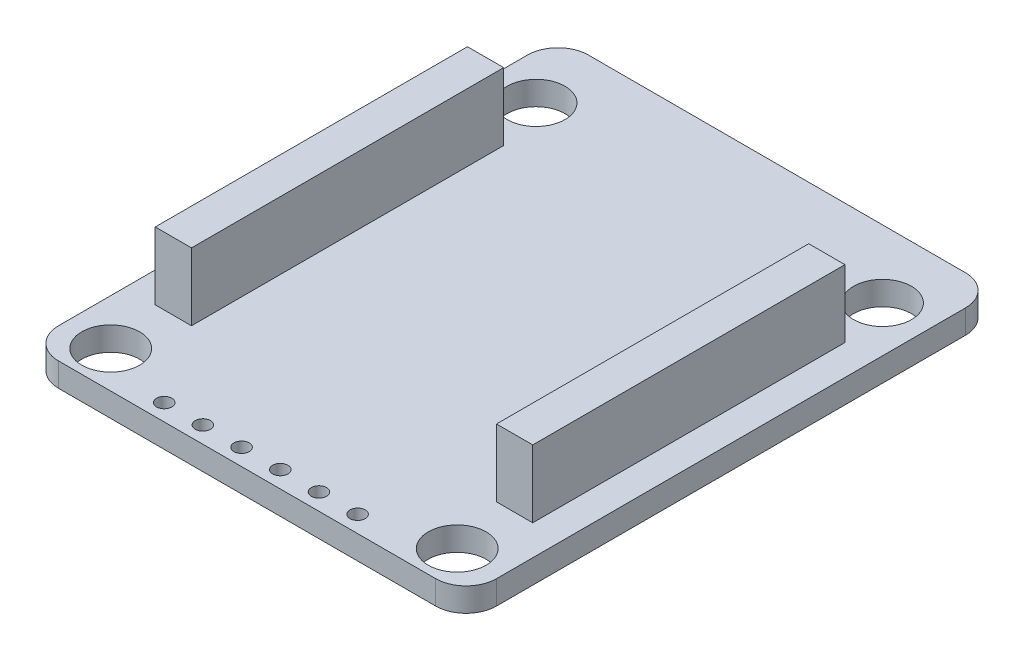
SolidWorks part; units mm, degrees
ref_plane "Front" through (0, 0, 0) normal (0, 0, 1) x (1, 0, 0)
ref_plane "Top" through (0, 0, 0) normal (0, 1, 0) x (1, 0, 0)
ref_plane "Right" through (0, 0, 0) normal (1, 0, 0) x (0, 0, -1)
sketch "Sketch1" plane through (0, 0, 0) normal (0, 1, 0) x (1, 0, 0)
  line L0 (-14.7218, -21.8882) -> (15.2782, -21.8882) construction
  line L1 (-14.38, -17.395) -> (14.38, -17.395)
  line L2 (-14.38, -17.395) -> (-14.38, 17.395)
  line L3 (-14.38, 17.395) -> (14.38, 17.395)
  line L4 (14.38, -17.395) -> (14.38, 17.395)
  line L5 (-14.38, -17.395) -> (14.38, 17.395) construction
  line L6 (-14.38, 17.395) -> (14.38, -17.395) construction
  point P0 (0, 0)
  dimension "D1" = 34.79
  dimension "D2" = 28.76
  dimension "D3" = 30
extrude "PCB" add sketch "Sketch1" along normal blind 1.56
hole_wizard "Ø3.8 (3.8) Diameter Hole4" positions "Sketch4" profile "Sketch5" hole size "Ø3.8" standard "ANSI Metric" end condition through all
sketch "Sketch4" plane through (0, 1.56, 0) normal (0, 1, 0) x (1, 0, 0)
  line L1 (-11.375, 12.955) -> (11.375, 12.955)
  line L2 (-11.375, 12.955) -> (-11.375, -14.975)
  line L3 (-11.375, -14.975) -> (11.375, -14.975)
  line L4 (11.375, 12.955) -> (11.375, -14.975)
  line L6 (0, 0) -> (0, 12.955) construction
  line L7 (-14.38, -17.395) -> (14.38, -17.395) construction
  point P0 (-11.375, 12.955)
  point P2 (11.375, 12.955)
  point P4 (-11.375, -14.975)
  point P6 (11.375, -14.975)
  dimension "D1" = 27.93
  dimension "D2" = 22.75
  dimension "D3" = 2.42
sketch "Sketch5" plane through (-11.375, 1.56, -12.955) normal (1, 0, 0) x (0, 0, 1)
  line L0 (0, 0) -> (0, 1.56)
  line L1 (0, 1.56) -> (1.9, 1.56)
  line L2 (1.9, 1.56) -> (1.9, 0)
  line L5 (1.9, 0) -> (0, 0)
  line L11 (0, -6.35) -> (0, 107.95) construction
  dimension "Thru Hole Dia." = 3.8
  dimension "Thru Hole Depth" = 1.56
sketch "Sketch7" plane through (0, 1.56, 0) normal (0, 1, 0) x (1, 0, 0)
  line L1 (-12.3935, 9.4686) -> (-10.0135, 9.4686)
  line L2 (-12.3935, 9.4686) -> (-12.3935, -11.0314)
  line L3 (-12.3935, -11.0314) -> (-10.0135, -11.0314)
  line L4 (-10.0135, 9.4686) -> (-10.0135, -11.0314)
  dimension "D2" = 2.38
  dimension "D3" = 20.5
extrude "Headers" add sketch "Sketch7" along normal blind 4.43
sketch "Sketch8" plane through (0, 1.56, 0) normal (0, 1, 0) x (1, 0, 0)
  line L0 (-6.5413, -16.295) -> (-4.0013, -16.295) construction
  line L1 (-4.0013, -16.295) -> (-1.4613, -16.295) construction
  line L2 (-1.4613, -16.295) -> (1.0787, -16.295) construction
  line L3 (1.0787, -16.295) -> (3.6187, -16.295) construction
  line L4 (3.6187, -16.295) -> (6.1587, -16.295) construction
  line L5 (-14.38, -17.395) -> (14.38, -17.395) construction
  circle A0 centre (-6.5413, -16.295) radius 0.5
  circle A1 centre (-4.0013, -16.295) radius 0.5
  circle A2 centre (-1.4613, -16.295) radius 0.5
  circle A3 centre (1.0787, -16.295) radius 0.5
  circle A4 centre (3.6187, -16.295) radius 0.5
  circle A5 centre (6.1587, -16.295) radius 0.5
  dimension "D3" = 1
  dimension "D1" = 2.54
  dimension "D2" = 1.1
extrude "Cut-Extrude1" cut sketch "Sketch8" against normal through all
mirror "Mirror1" about plane through (0, 0, 0) normal (1, 0, 0) of "Headers"
fillet "Fillet1" radius 2 4 edges at (14.38, 0.78, -17.395) (14.38, 0.78, 17.395) (-14.38, 0.78, 17.395) (-14.38, 0.78, -17.395)
